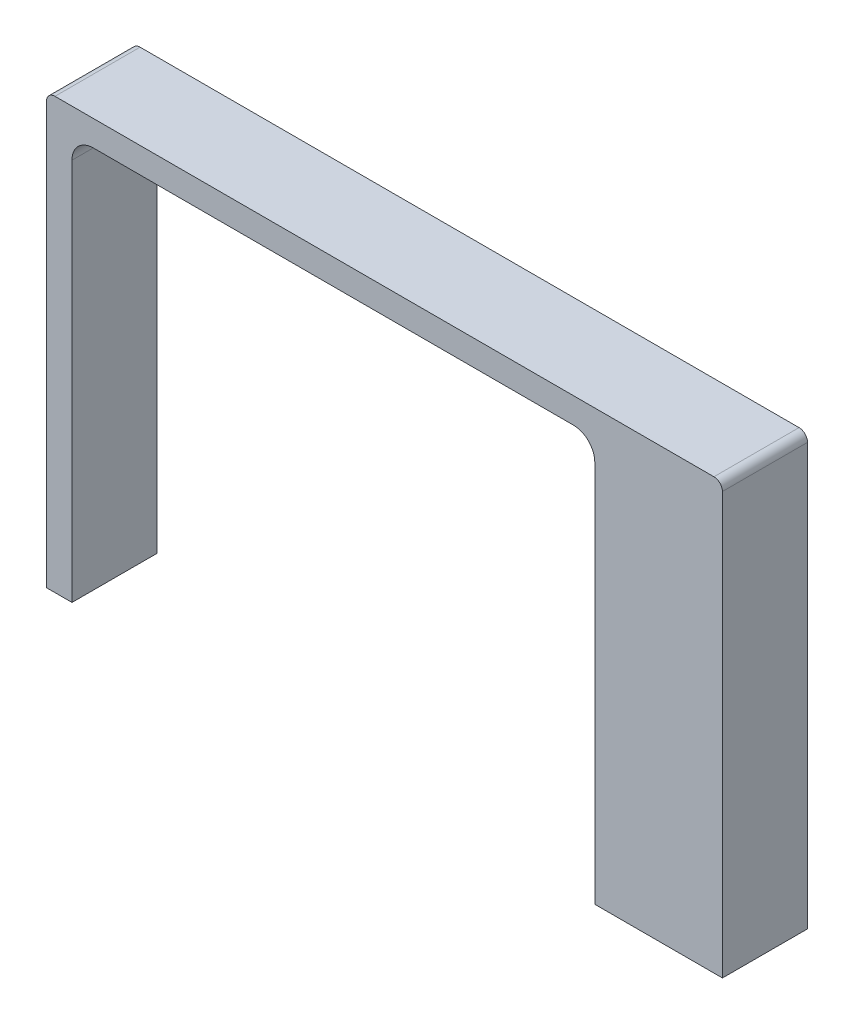
SolidWorks part; units mm, degrees
ref_plane "Front" through (0, 0, 0) normal (0, 0, 1) x (1, 0, 0)
ref_plane "Top" through (0, 0, 0) normal (0, 1, 0) x (1, 0, 0)
ref_plane "Right" through (0, 0, 0) normal (1, 0, 0) x (0, 0, -1)
sketch "Sketch1" plane through (0, 0, 0) normal (0, 0, 1) x (1, 0, 0)
  line L0 (62.7634, -64.135) -> (100.8634, -64.135)
  line L1 (-100.8634, 64.135) -> (100.8634, 64.135)
  line L2 (-100.8634, 64.135) -> (-100.8634, -64.135)
  line L3 (-100.8634, -64.135) -> (-93.2434, -64.135)
  line L4 (100.8634, 64.135) -> (100.8634, -64.135)
  line L5 (-100.8634, 64.135) -> (100.8634, -64.135) construction
  line L6 (-100.8634, -64.135) -> (100.8634, 64.135) construction
  line L7 (62.7634, 56.515) -> (-93.2434, 56.515)
  line L8 (62.7634, 56.515) -> (62.7634, -64.135)
  line L10 (-93.2434, 56.515) -> (-93.2434, -64.135)
  point P0 (0, 0)
  dimension "D1" = 7.62
  dimension "D2" = 156.0068
  dimension "D3" = 7.62
  dimension "D4" = 38.1
  dimension "D5" = 128.27
  dimension "D6" = 201.7268
  dimension "D7" = 128.27
extrude "Boss-Extrude1" add sketch "Sketch1" along normal blind 25.4
fillet "Fillet1" radius 6.35 2 edges at (-93.2434, 56.515, 12.7) (62.7634, 56.515, 12.7)
fillet "Fillet2" radius 2.54 2 edges at (-100.8634, 64.135, 12.7) (100.8634, 64.135, 12.7)
